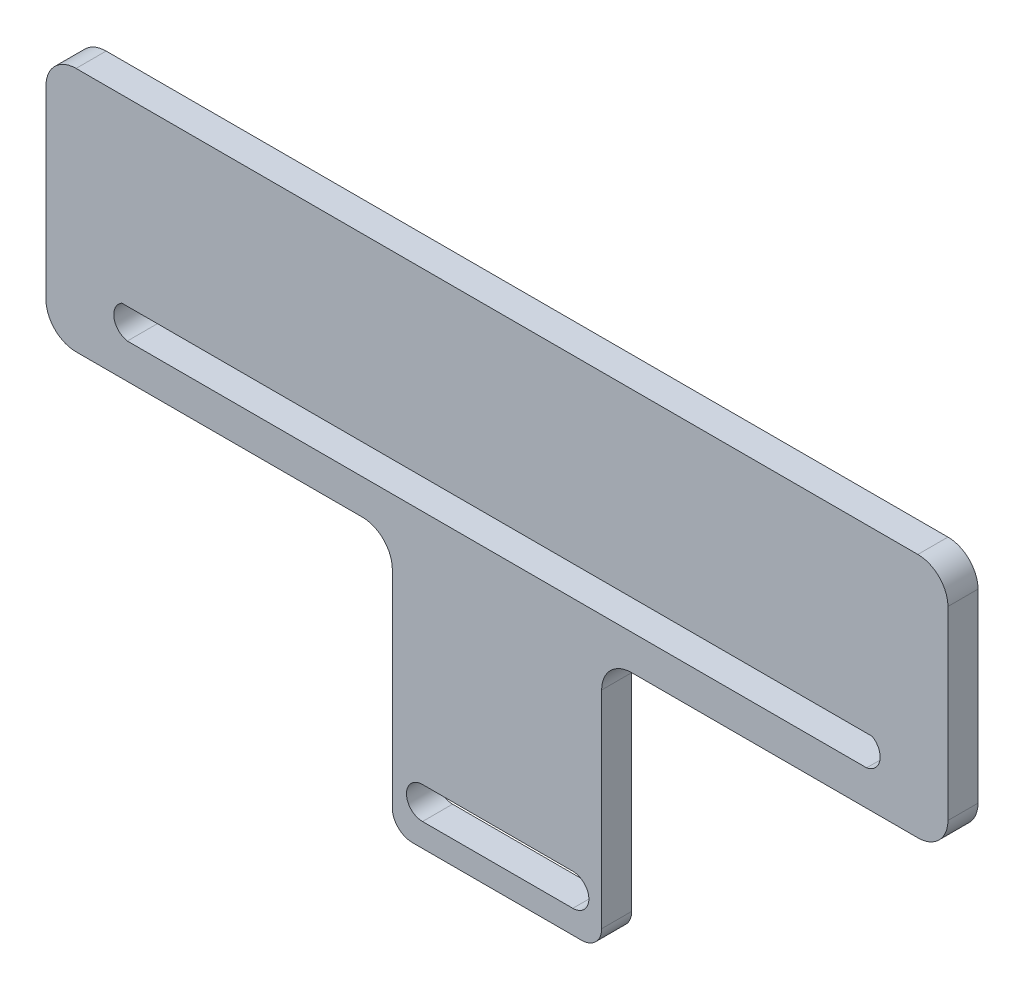
SolidWorks part; units mm, degrees
ref_plane "前视基准面" through (0, 0, 0) normal (0, 0, 1) x (1, 0, 0)
ref_plane "上视基准面" through (0, 0, 0) normal (0, 1, 0) x (1, 0, 0)
ref_plane "右视基准面" through (0, 0, 0) normal (1, 0, 0) x (0, 0, -1)
other "Configuration Table"
sketch "草图1" plane through (0, 0, 0) normal (0, 0, 1) x (1, 0, 0)
  line L0 (-7.4307, 0) -> (7.5693, 0) construction
  line L1 (-8.4437, -3.9288) -> (8.4437, -3.9288)
  line L2 (-10.4437, -1.9288) -> (-10.4437, 1.7024)
  line L4 (10.4437, -1.9288) -> (10.4437, 1.7024)
  line L5 (-10.4437, -3.9288) -> (12.8451, 4.8322) construction
  line L6 (-12.2068, 4.5921) -> (10.4437, -3.9288) construction
  line L7 (-7.4307, 1.6) -> (7.5693, 1.6)
  line L8 (-7.4307, -1.6) -> (7.5693, -1.6)
  line L9 (0, 60.8919) -> (0, -17.1926) construction
  line L10 (-33.4765, 0) -> (36.5626, 0) construction
  line L14 (-13.4437, 21.7024) -> (-42, 21.7024)
  line L17 (-10.4437, 1.7024) -> (-10.4437, 18.7024)
  line L18 (-45, 24.7024) -> (-45, 43.1965)
  line L19 (-42, 46.1965) -> (42, 46.1965)
  line L20 (0, 26.7996) -> (-36.6104, 26.7996) construction
  line L21 (36.8839, 25.1965) -> (-36.8839, 25.1965)
  line L22 (37.4431, 28.1965) -> (-37.4431, 28.1965)
  line L23 (10.4437, 1.7024) -> (10.4437, 18.7024)
  line L24 (13.4437, 21.7024) -> (42, 21.7024)
  line L25 (45, 24.7024) -> (45, 43.1965)
  arc A0 (-7.4307, 1.6) -> (-7.4307, -1.6) centre (-7.4307, 0) ccw
  arc A1 (7.5693, -1.6) -> (7.5693, 1.6) centre (7.5693, 0) ccw
  arc A4 (8.4437, -3.9288) -> (10.4437, -1.9288) centre (8.4437, -1.9288) ccw
  arc A5 (-8.4437, -3.9288) -> (-10.4437, -1.9288) centre (-8.4437, -1.9288) cw
  arc A12 (-37.4431, 28.1965) -> (-36.8839, 25.1965) centre (-36.6104, 26.7996) ccw
  arc A13 (-45, 43.1965) -> (-42, 46.1965) centre (-42, 43.1965) cw
  arc A14 (-42, 21.7024) -> (-45, 24.7024) centre (-42, 24.7024) cw
  arc A15 (-10.4437, 18.7024) -> (-13.4437, 21.7024) centre (-13.4437, 18.7024) ccw
  arc A16 (37.4431, 28.1965) -> (36.8839, 25.1965) centre (36.6104, 26.7996) cw
  arc A17 (10.4437, 18.7024) -> (13.4437, 21.7024) centre (13.4437, 18.7024) cw
  arc A18 (42, 21.7024) -> (45, 24.7024) centre (42, 24.7024) ccw
  arc A19 (45, 43.1965) -> (42, 46.1965) centre (42, 43.1965) ccw
  point P0 (0, 0)
  point P8 (0.0693, 0)
  point P31 (-18.4513, 26.8278)
  point P33 (0, 25)
  point P37 (0, 46.1965)
  point P40 (-45, 46.1965)
  point P45 (-10.4437, 21.7024)
  point P47 (0, 25.1965)
  point P49 (0, 23)
  point P50 (0, 28.1965)
  point P57 (0, 46.1965)
  dimension "D2" = 3
  dimension "D3" = 3.4941
  dimension "D4" = 20
  dimension "D6" = 45
  dimension "D7" = 3.2
  dimension "D8" = 3
  dimension "D1" = 15
  dimension "D5" = 18
extrude "凸台-拉伸2" add sketch "草图1" along normal blind 3
